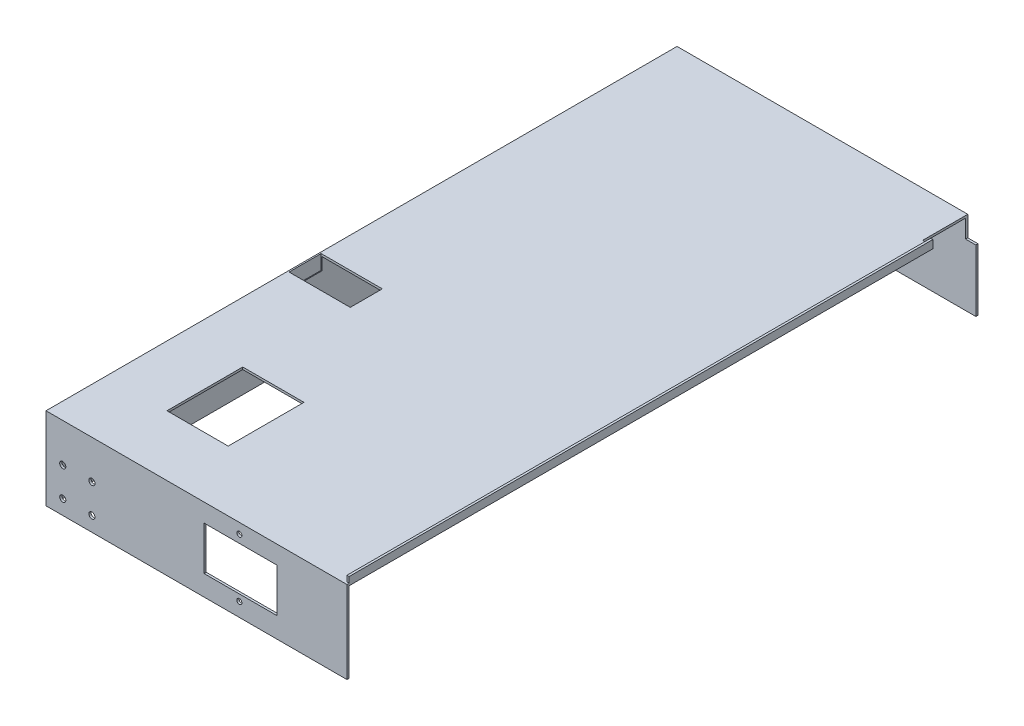
SolidWorks part; units mm, degrees
ref_plane "Front Plane" through (0, 0, 0) normal (0, 0, 1) x (1, 0, 0)
ref_plane "Top Plane" through (0, 0, 0) normal (0, 1, 0) x (1, 0, 0)
ref_plane "Right Plane" through (0, 0, 0) normal (1, 0, 0) x (0, 0, -1)
sketch "Sketch4" plane through (0, 0, 0) normal (0, 1, 0) x (1, 0, 0)
  line L0 (139.3737, 430) -> (344.3737, 430)
  line L1 (344.3737, 430) -> (344.3737, 0)
  line L2 (344.3737, 0) -> (139.3737, 0)
  line L3 (139.3737, 0) -> (139.3737, 65)
  line L7 (139.3737, 230) -> (139.3737, 430)
  line L8 (139.3737, 230) -> (139.3737, 65)
  line L10 (179.3737, 40) -> (221.3737, 40)
  line L11 (179.3737, 40) -> (179.3737, 92)
  line L12 (179.3737, 92) -> (221.3737, 92)
  line L13 (221.3737, 40) -> (221.3737, 92)
  dimension "D1" = 52
  dimension "D2" = 430
  dimension "D3" = 42
  dimension "D5" = 205
  dimension "D6" = 205
extrude "Boss-Extrude4" add sketch "Sketch4" along normal blind 1.5 separate body
sketch "Sketch5" plane through (0, 0, 0) normal (0, 0, 1) x (1, 0, 0)
  line L1 (139.3737, 1.5) -> (344.3737, 1.5)
  line L2 (139.3737, 1.5) -> (139.3737, -55)
  line L3 (139.3737, -55) -> (344.3737, -55)
  line L4 (344.3737, 1.5) -> (344.3737, -55)
  dimension "D1" = 56.5
sketch "Sketch7" plane through (0, 0, -430) normal (0, 0, -1) x (-1, 0, 0)
  line L1 (-139.3737, 1.5) -> (-344.3737, 1.5)
  line L2 (-139.3737, 1.5) -> (-139.3737, -55)
  line L3 (-139.3737, -55) -> (-344.3737, -55)
  line L4 (-344.3737, 1.5) -> (-344.3737, -55)
  dimension "D1" = 56.5
sketch "Sketch8" plane through (0, 1.5, 0) normal (0, 1, 0) x (1, 0, 0)
  line L0 (139.3737, 430) -> (344.3737, 430) construction
  line L1 (344.3737, 0) -> (342.8737, 0)
  line L2 (344.3737, 0) -> (344.3737, 430)
  line L3 (344.3737, 430) -> (342.8737, 430)
  line L4 (342.8737, 0) -> (342.8737, 430)
  dimension "D1" = 1.5
  dimension "D2" = 430
extrude "Boss-Extrude5" add sketch "Sketch5" along normal blind 1.5 and the other way blind 0.0001
extrude "Boss-Extrude14" add sketch "Sketch8" along normal blind 4
extrude "Boss-Extrude18" add sketch "Sketch7" along normal blind 1.5
sketch "Sketch9" plane through (139.3737, 0, 0) normal (-1, 0, 0) x (0, 0, 1)
  line L1 (-431.5, 1.5) -> (1.5, 1.5)
  line L2 (-431.5, 1.5) -> (-431.5, -55)
  line L3 (-431.5, -55) -> (1.5, -55)
  line L4 (1.5, 1.5) -> (1.5, -55)
extrude "Boss-Extrude19" add sketch "Sketch9" along normal blind 1.5
sketch "Sketch10" plane through (0, 0, 1.5) normal (0, 0, 1) x (1, 0, 0)
  circle A0 centre (169.3737, -45) radius 2.1
sketch "Sketch11" plane through (0, 0, 1.5) normal (0, 0, 1) x (1, 0, 0)
  line L1 (137.8737, -55) -> (137.8737, 1.5) construction
  line L2 (139.3737, -55) -> (344.3737, -55) construction
  circle A0 centre (149.3737, -45) radius 2.1
  dimension "D1" = 11.5
  dimension "D2" = 10
sketch "Sketch12" plane through (0, 0, 1.5) normal (0, 0, 1) x (1, 0, 0)
  line L0 (137.8737, -55) -> (137.8737, 1.5) construction
  line L1 (139.3737, 1.5) -> (344.3737, 1.5) construction
  circle A0 centre (149.3737, -25) radius 2.1
  dimension "D1" = 11.5
  dimension "D2" = 26.5
sketch "Sketch14" plane through (0, 0, 1.5) normal (0, 0, 1) x (1, 0, 0)
  line L0 (137.8737, -55) -> (137.8737, 1.5) construction
  line L1 (139.3737, 1.5) -> (344.3737, 1.5) construction
  circle A0 centre (169.3737, -25) radius 2.1
  dimension "D1" = 31.5
  dimension "D2" = 26.5
sketch "Sketch15" plane through (0, 0, -431.5) normal (0, 0, -1) x (-1, 0, 0)
  circle A0 centre (-169.3737, -25) radius 2.1
  circle A1 centre (-149.3737, -25) radius 2.1
  circle A2 centre (-169.3737, -45) radius 2.1
  circle A3 centre (-149.3737, -45) radius 2.1
extrude "Cut-Extrude1" cut sketch "Sketch15" against normal blind 10
extrude "Cut-Extrude2" cut sketch "Sketch14" against normal blind 10
extrude "Cut-Extrude3" cut sketch "Sketch12" against normal blind 10
extrude "Cut-Extrude4" cut sketch "Sketch10" against normal blind 10
extrude "Cut-Extrude5" cut sketch "Sketch11" against normal blind 10
sketch "Sketch17" plane through (0, 1.5, 0) normal (0, 1, 0) x (1, 0, 0)
  line L1 (138.8371, 186.3117) -> (180.8371, 186.3117)
  line L2 (138.8371, 186.3117) -> (138.8371, 164.3117)
  line L3 (138.8371, 164.3117) -> (180.8371, 164.3117)
  line L4 (180.8371, 186.3117) -> (180.8371, 164.3117)
extrude "Cut-Extrude6" cut sketch "Sketch17" against normal blind 10
sketch "Sketch18" plane through (0, 0, 1.5) normal (0, 0, 1) x (1, 0, 0)
  line L0 (139.3737, -55) -> (344.3737, -55) construction
  line L1 (246.3048, -11) -> (296.3737, -11)
  line L2 (246.3048, -11) -> (246.3048, -41)
  line L3 (246.3048, -41) -> (296.3737, -41)
  line L4 (296.3737, -11) -> (296.3737, -41)
  line L5 (344.3737, -55) -> (344.3737, 1.5) construction
  dimension "D1" = 14
  dimension "D2" = 48
sketch "Sketch19" plane through (0, 0, 1.5) normal (0, 0, 1) x (1, 0, 0)
  line L0 (139.3737, -55) -> (344.3737, -55) construction
  line L1 (139.3737, 1.5) -> (344.3737, 1.5) construction
  circle A0 centre (270.5434, -5.5) radius 1.75
  circle A1 centre (270.5434, -45.5) radius 1.75
  dimension "D1" = 3.5
  dimension "D2" = 9.5
  dimension "D3" = 7
  dimension "D4" = 40
extrude "Cut-Extrude7" cut sketch "Sketch18" against normal blind 10
extrude "Cut-Extrude8" cut sketch "Sketch19" against normal blind 10
sketch "Sketch23" plane through (0, 0, -431.5) normal (0, 0, -1) x (-1, 0, 0)
  line L1 (-344.3737, 5.5) -> (-337.3737, 5.5)
  line L2 (-344.3737, 5.5) -> (-344.3737, -12.5)
  line L3 (-344.3737, -12.5) -> (-337.3737, -12.5)
  line L4 (-337.3737, 5.5) -> (-337.3737, -12.5)
extrude "Cut-Extrude10" cut sketch "Sketch23" against normal blind 31
sketch "Sketch24" [suppressed] plane through (0, 0, 1.5) normal (0, 0, 1) x (1, 0, 0)
  line L1 (344.3737, 5.5) -> (337.3737, 5.5)
  line L2 (344.3737, 5.5) -> (344.3737, -12.5)
  line L3 (344.3737, -12.5) -> (337.3737, -12.5)
  line L4 (337.3737, 5.5) -> (337.3737, -12.5)
extrude "Cut-Extrude11" [suppressed] cut sketch "Sketch24" against normal blind 31
